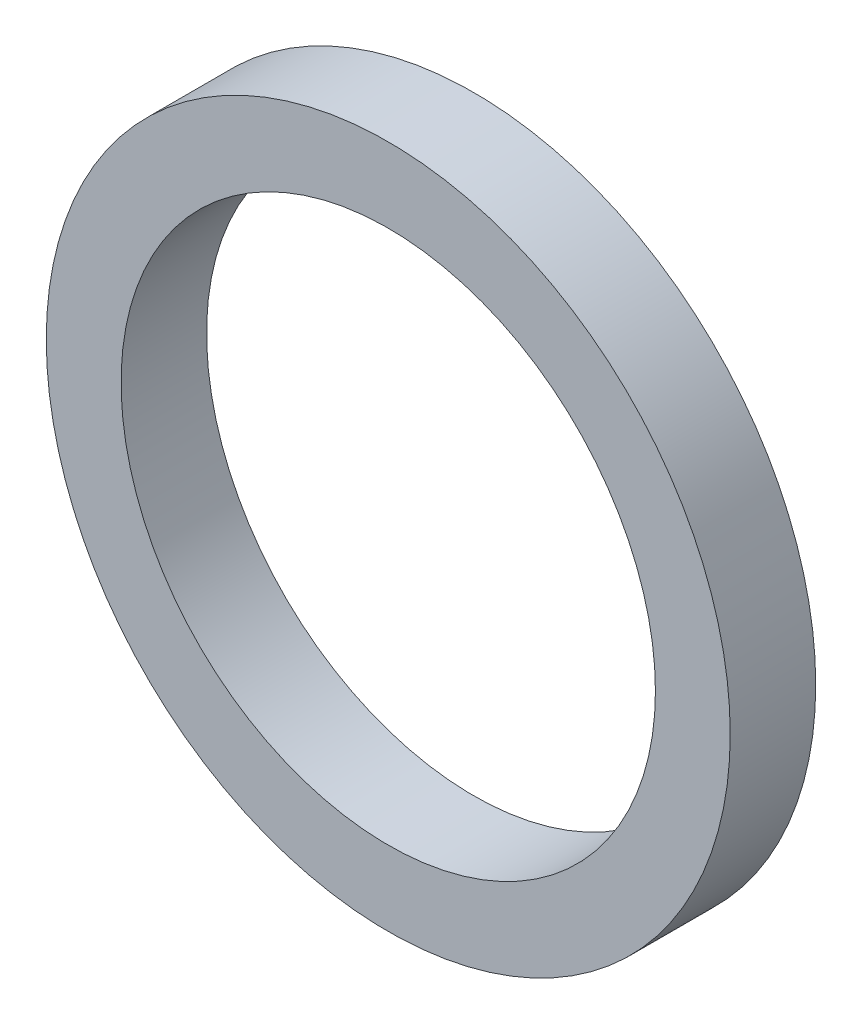
SolidWorks part; units mm, degrees
ref_plane "前视基准面" through (0, 0, 0) normal (0, 0, 1) x (1, 0, 0)
ref_plane "上视基准面" through (0, 0, 0) normal (0, 1, 0) x (1, 0, 0)
ref_plane "右视基准面" through (0, 0, 0) normal (1, 0, 0) x (0, 0, -1)
other "Configuration Table"
sketch "草图1" plane through (0, 0, 0) normal (0, 0, 1) x (1, 0, 0)
  circle A0 centre (0, 0) radius 12.5
  circle A1 centre (0, 0) radius 16
  dimension "D1" = 25
  dimension "D2" = 32
extrude "凸台-拉伸1" add sketch "草图1" along normal blind 4
